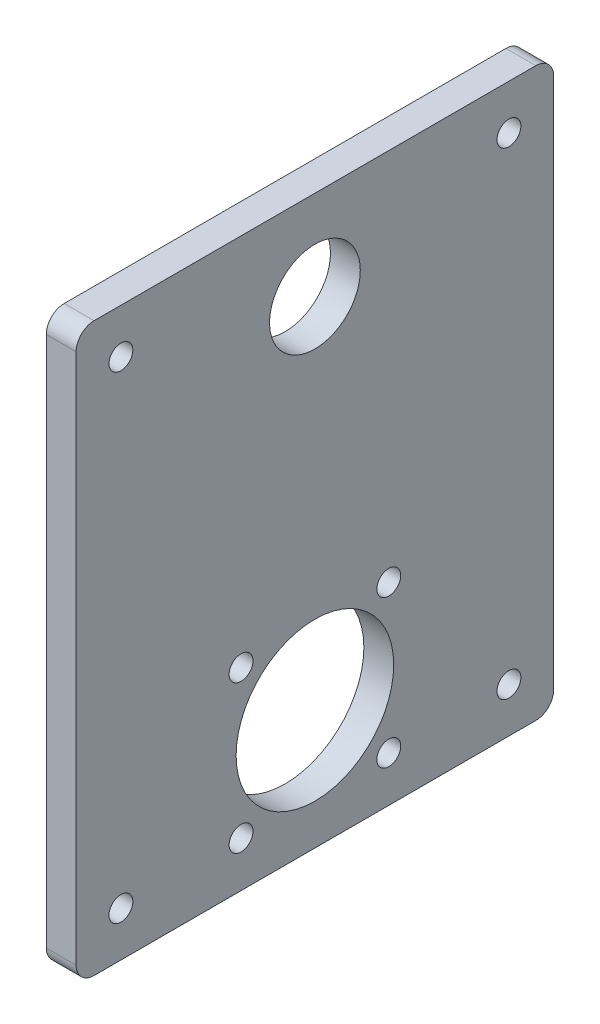
SolidWorks part; units mm, degrees
material "ﾎﾟﾘ塩化ﾋﾞﾆﾙ(PVC)硬質"
ref_plane "正面" through (0, 0, 0) normal (0, 0, 1) x (1, 0, 0)
ref_plane "平面" through (0, 0, 0) normal (0, 1, 0) x (1, 0, 0)
ref_plane "右側面" through (0, 0, 0) normal (1, 0, 0) x (0, 0, -1)
sketch "ｽｹｯﾁ1" plane through (0, 0, 0) normal (1, 0, 0) x (0, 0, -1)
  line L0 (0, 0) -> (0, 5298.4994) construction
  line L1 (-40, -47.5) -> (40, -47.5)
  line L2 (-40, -47.5) -> (-40, 47.5)
  line L3 (-40, 47.5) -> (40, 47.5)
  line L4 (40, -47.5) -> (40, 47.5)
  line L5 (-40, -47.5) -> (40, 47.5) construction
  line L6 (-40, 47.5) -> (40, -47.5) construction
  line L7 (0, 0) -> (5298.4994, 0) construction
  line L8 (0, -27.5) -> (12.3744, -15.1256) construction
  line L9 (0, -27.5) -> (12.3744, -39.8744) construction
  line L10 (0, -27.5) -> (17.5, -27.5) construction
  line L11 (32.5, 47.5) -> (32.5, -47.5) construction
  circle A0 centre (0, 32.5) radius 40 construction
  circle A1 centre (0, -27.5) radius 20 construction
  circle A2 centre (0, -27.5) radius 17.5 construction
  circle A7 centre (0, 32.5) radius 7.6
  circle A8 centre (12.3744, -15.1256) radius 2
  circle A9 centre (12.3744, -39.8744) radius 2
  circle A10 centre (-12.3744, -39.8744) radius 2
  circle A11 centre (-12.3744, -15.1256) radius 2
  circle A12 centre (0, -27.5) radius 13.2
  circle A13 centre (32.5, 40) radius 2
  circle A14 centre (32.5, -40) radius 2
  circle A15 centre (-32.5, -40) radius 2
  circle A16 centre (-32.5, 40) radius 2
  point P0 (0, 0)
  dimension "D1" = 80
  dimension "D2" = 40
  dimension "D3" = 35
  dimension "D4" = 7.5
  dimension "D6" = 80
  dimension "D7" = 15.2
  dimension "D8" = 15
  dimension "D5" = 4
  dimension "D9" = 26.4
  dimension "D10" = 7.5
  dimension "D11" = 4
  dimension "D12" = 80
extrude "ﾎﾞｽ - 押し出し1" add sketch "ｽｹｯﾁ1" along normal blind 5
fillet "ﾌｨﾚｯﾄ1" radius 3 4 edges at (2.5, -47.5, 40) (2.5, -47.5, -40) (2.5, 47.5, -40) (2.5, 47.5, 40)
